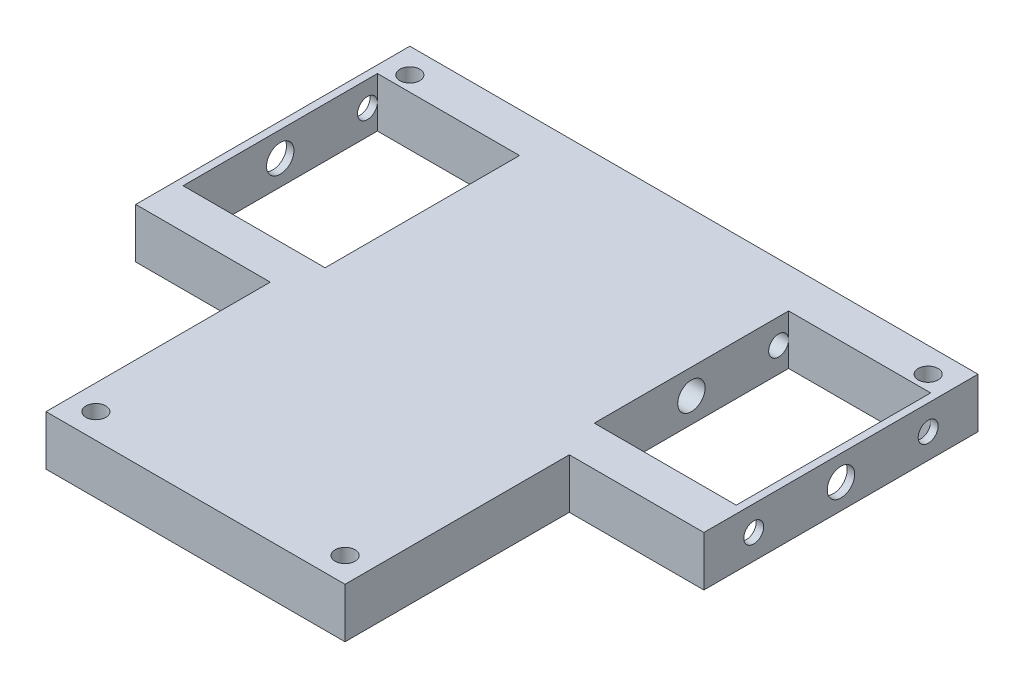
SolidWorks part; units mm, degrees
ref_plane "Front Plane" through (0, 0, 0) normal (0, 0, 1) x (1, 0, 0)
ref_plane "Top Plane" through (0, 0, 0) normal (0, 1, 0) x (1, 0, 0)
ref_plane "Right Plane" through (0, 0, 0) normal (1, 0, 0) x (0, 0, -1)
sketch "Sketch1" plane through (0, 0, 0) normal (0, 1, 0) x (1, 0, 0)
  line L0 (0, 0) -> (0, 226.5914) construction
  line L1 (30, 0) -> (-30, 0)
  line L2 (-30, 0) -> (-30, 45)
  line L3 (-30, 45) -> (-57, 45)
  line L4 (-57, 45) -> (-57, 100)
  line L5 (-57, 100) -> (57, 100)
  line L6 (30, 0) -> (30, 45)
  line L7 (30, 45) -> (57, 45)
  line L8 (57, 45) -> (57, 100)
  point P11 (0, 0)
  point P14 (0, 100)
  dimension "D1" = 30
  dimension "D2" = 45
  dimension "D3" = 55
extrude "Boss-Extrude1" add sketch "Sketch1" along normal blind 10 contours L3 L4 L5 L8 L7 L6 L1 L2
sketch "Sketch2" plane through (0, 10, 0) normal (0, 1, 0) x (1, 0, 0)
  line L0 (-57, 72.5) -> (57, 72.5) construction
  line L1 (-57, 45) -> (-57, 100) construction
  line L2 (57, 45) -> (57, 100) construction
  line L3 (-55.5, 53) -> (-55.5, 92)
  line L4 (-55.5, 92) -> (-27, 92)
  line L5 (-27, 92) -> (-27, 53)
  line L6 (-55.5, 53) -> (-27, 53)
  line L7 (0, 100) -> (0, 0) construction
  line L8 (-57, 100) -> (57, 100) construction
  line L9 (27, 92) -> (27, 53)
  line L10 (55.5, 53) -> (27, 53)
  line L11 (55.5, 53) -> (55.5, 92)
  line L12 (55.5, 92) -> (27, 92)
  line L13 (-30, 0) -> (-30, 45) construction
  line L15 (30, 0) -> (-30, 0) construction
  circle A0 centre (-52, 95) radius 2
  circle A1 centre (52, 95) radius 2
  circle A2 centre (-25, 5) radius 2
  circle A3 centre (25, 5) radius 2
  point P11 (-27, 72.5)
  point P12 (-55.5, 72.5)
  point P31 (0, 0)
  dimension "D4" = 4
  dimension "D7" = 4
  dimension "D1" = 1.5
  dimension "D2" = 28.5
  dimension "D3" = 39
  dimension "D5" = 5
  dimension "D6" = 5
  dimension "D8" = 5
  dimension "D9" = 5
extrude "Cut-Extrude1" cut sketch "Sketch2" against normal through all both and the other way through all contours A1 | A2 | A3 | L5 L6 L3 L4 | L9 L10 L11 L12 | A0
sketch "Sketch5" plane through (57, 0, 0) normal (1, 0, 0) x (0, 0, -1)
  line L0 (72.5, 10) -> (72.5, 0) construction
  line L1 (45, 10) -> (100, 10) construction
  line L2 (45, 0) -> (100, 0) construction
  line L3 (45, 5) -> (100, 5) construction
  line L4 (45, 10) -> (45, 0) construction
  line L5 (100, 10) -> (100, 0) construction
  circle A0 centre (55, 5) radius 2
  circle A1 centre (90, 5) radius 2
  circle A2 centre (72.5, 5) radius 2.75
  point P14 (72.5, 5)
  dimension "D1" = 17.5
  dimension "D2" = 5.5
extrude "Cut-Extrude2" cut sketch "Sketch5" against normal through all
